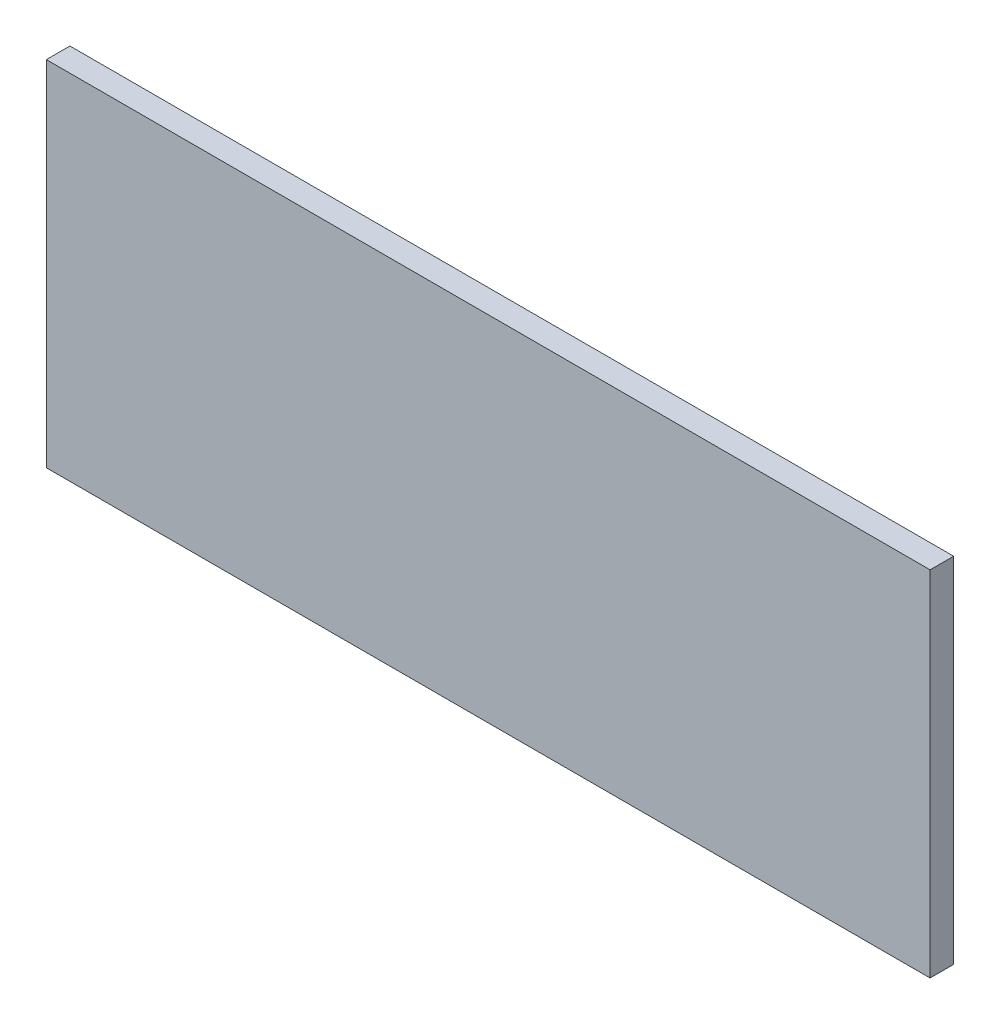
SolidWorks part; units mm, degrees
ref_plane "Front Plane" through (0, 0, 0) normal (0, 0, 1) x (1, 0, 0)
ref_plane "Top Plane" through (0, 0, 0) normal (0, 1, 0) x (1, 0, 0)
ref_plane "Right Plane" through (0, 0, 0) normal (1, 0, 0) x (0, 0, -1)
sketch "Sketch1" plane through (0, 0, 0) normal (1, 0, 0) x (0, 0, -1)
  line L1 (-2, -30) -> (2, -30)
  line L2 (-2, -30) -> (-2, 30)
  line L3 (-2, 30) -> (2, 30)
  line L4 (2, -30) -> (2, 30)
  line L5 (-2, -30) -> (2, 30) construction
  line L6 (-2, 30) -> (2, -30) construction
  point P0 (0, 0)
  dimension "D1" = 60
  dimension "D2" = 4
extrude "Boss-Extrude1" add sketch "Sketch1" along normal mid plane 150
